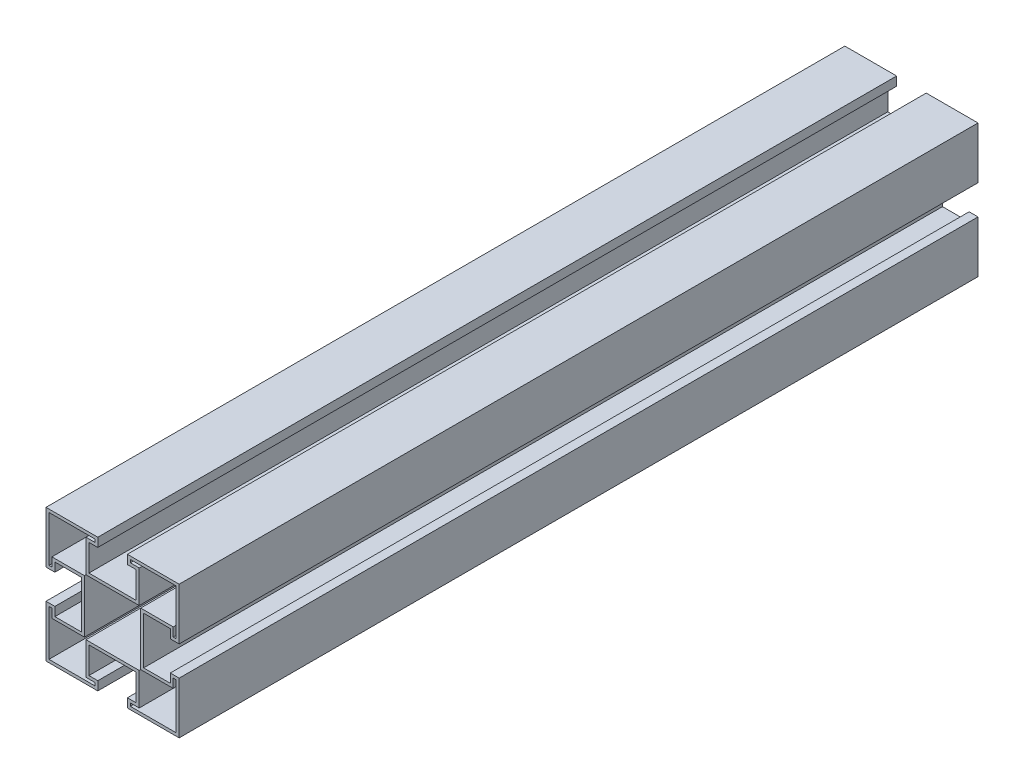
SolidWorks part; units mm, degrees
ref_plane "Ön Düzlem" through (0, 0, 0) normal (0, 0, 1) x (1, 0, 0)
ref_plane "Üst Düzlem" through (0, 0, 0) normal (0, 1, 0) x (1, 0, 0)
ref_plane "Sağ Düzlem" through (0, 0, 0) normal (1, 0, 0) x (0, 0, -1)
sketch "Sketch1" plane through (0, 0, 0) normal (0, 0, 1) x (1, 0, 0)
  line L0 (-5, 22.5) -> (-5, 19.5)
  line L1 (22.5, 22.5) -> (5, 22.5)
  line L2 (22.5, 22.5) -> (22.5, 5)
  line L3 (22.5, -22.5) -> (5, -22.5)
  line L4 (-22.5, 22.5) -> (-22.5, 5)
  line L5 (22.5, 22.5) -> (-22.5, -22.5) construction
  line L6 (22.5, -22.5) -> (-22.5, 22.5) construction
  line L7 (-5, 19.5) -> (-8, 19.5)
  line L8 (-8, 19.5) -> (-8, 10.5)
  line L9 (-8, 10.5) -> (8, 10.5)
  line L10 (8, 10.5) -> (8, 19.5)
  line L11 (8, 19.5) -> (5, 19.5)
  line L12 (5, 19.5) -> (5, 22.5)
  line L13 (22.5, 5) -> (19.5, 5)
  line L14 (19.5, 5) -> (19.5, 8)
  line L15 (19.5, 8) -> (10.5, 8)
  line L16 (10.5, 8) -> (10.5, -8)
  line L17 (10.5, -8) -> (19.5, -8)
  line L18 (19.5, -8) -> (19.5, -5)
  line L19 (19.5, -5) -> (22.5, -5)
  line L20 (0, 0) -> (22.5, 0) construction
  line L21 (0, 22.5) -> (0, 0) construction
  line L22 (-19.5, 5) -> (-19.5, 8)
  line L23 (-10.5, 8) -> (-10.5, -8)
  line L24 (-19.5, -8) -> (-19.5, -5)
  line L25 (-10.5, -8) -> (-19.5, -8)
  line L26 (-19.5, -5) -> (-22.5, -5)
  line L27 (-22.5, 5) -> (-19.5, 5)
  line L28 (-19.5, 8) -> (-10.5, 8)
  line L29 (-5, -22.5) -> (-5, -19.5)
  line L30 (5, -19.5) -> (5, -22.5)
  line L31 (8, -19.5) -> (5, -19.5)
  line L32 (8, -10.5) -> (8, -19.5)
  line L33 (-8, -10.5) -> (8, -10.5)
  line L34 (-8, -19.5) -> (-8, -10.5)
  line L35 (-5, -19.5) -> (-8, -19.5)
  line L36 (-5, -22.5) -> (-22.5, -22.5)
  line L37 (22.5, -5) -> (22.5, -22.5)
  line L38 (-5, 22.5) -> (-22.5, 22.5)
  line L39 (-22.5, -5) -> (-22.5, -22.5)
  line L40 (-5, 22.5) -> (5, 22.5) construction
  line L41 (22.5, 5) -> (22.5, -5) construction
  line L42 (-6, 21.5) -> (-21.5, 21.5)
  line L43 (-21.5, 21.5) -> (-21.5, 6)
  line L44 (-21.5, 6) -> (-20.5, 6)
  line L45 (-20.5, 6) -> (-20.5, 9)
  line L46 (-20.5, 9) -> (-9.5, 9)
  line L47 (-9.5, 9) -> (-9.5, -9)
  line L48 (-9.5, -9) -> (-20.5, -9)
  line L49 (-20.5, -9) -> (-20.5, -6)
  line L50 (-20.5, -6) -> (-21.5, -6)
  line L51 (-21.5, -6) -> (-21.5, -21.5)
  line L52 (-6, -21.5) -> (-21.5, -21.5)
  line L53 (-6, -21.5) -> (-6, -20.5)
  line L54 (-6, -20.5) -> (-9, -20.5)
  line L55 (-9, -20.5) -> (-9, -9.5)
  line L56 (-9, -9.5) -> (9, -9.5)
  line L57 (9, -9.5) -> (9, -20.5)
  line L58 (9, -20.5) -> (6, -20.5)
  line L59 (6, -20.5) -> (6, -21.5)
  line L60 (21.5, -21.5) -> (6, -21.5)
  line L61 (21.5, -6) -> (21.5, -21.5)
  line L62 (20.5, -6) -> (21.5, -6)
  line L63 (20.5, -9) -> (20.5, -6)
  line L64 (9.5, -9) -> (20.5, -9)
  line L65 (9.5, 9) -> (9.5, -9)
  line L66 (20.5, 9) -> (9.5, 9)
  line L67 (20.5, 6) -> (20.5, 9)
  line L68 (21.5, 6) -> (20.5, 6)
  line L69 (21.5, 21.5) -> (21.5, 6)
  line L70 (21.5, 21.5) -> (6, 21.5)
  line L71 (6, 20.5) -> (6, 21.5)
  line L72 (9, 20.5) -> (6, 20.5)
  line L73 (9, 9.5) -> (9, 20.5)
  line L74 (-9, 9.5) -> (9, 9.5)
  line L75 (-9, 20.5) -> (-9, 9.5)
  line L76 (-6, 20.5) -> (-9, 20.5)
  line L77 (-6, 21.5) -> (-6, 20.5)
  point P0 (0, 0)
  dimension "D1" = 45
  dimension "D2" = 3
  dimension "D3" = 10
  dimension "D4" = 10
  dimension "D5" = 12
  dimension "D6" = 12
  dimension "D7" = 1
extrude "Boss-Extrude2" add sketch "Sketch1" along normal mid plane 270 contours L26 L39 L36 L29 L35 L34 L33 L32 L31 L30 L3 L37 L19 L18 L17 L16 L15 L14 L13 L2 L1 L12 L11 L10 L9 L8 L7 L0 L38 L4 L27 L22 L28 L23 L25 L24 L42 L77 L76 L75 L74 L73 L72 L71 L70 L69 L68 L67 L66 L65
sketch "Sketch2" plane through (0, 22.5, 0) normal (0, 1, 0) x (1, 0, 0)
  line L0 (0, 135) -> (0, -135) construction
  line L1 (-8, 135) -> (8, 135) construction
  line L2 (-8, -135) -> (8, -135) construction
ref_plane "Plane1" through (0, 0, 0) normal (-1, 0, 0) x (0, 0, 1)
sketch "Sketch3" plane through (-22.5, 0, 0) normal (-1, 0, 0) x (0, 0, 1)
  line L0 (135, 0) -> (-135, 0) construction
  line L1 (135, 8) -> (135, -8) construction
  line L2 (-135, 8) -> (-135, -8) construction
sketch "Sketch4" plane through (22.5, 0, 0) normal (1, 0, 0) x (0, 0, -1)
  line L0 (135, 0) -> (-135, 0) construction
ref_plane "Plane2" through (0, 0, 0) normal (0, 1, 0) x (1, 0, 0)
ref_plane "Plane3" through (0, 0, 0) normal (0, 1, 0) x (1, 0, 0)
